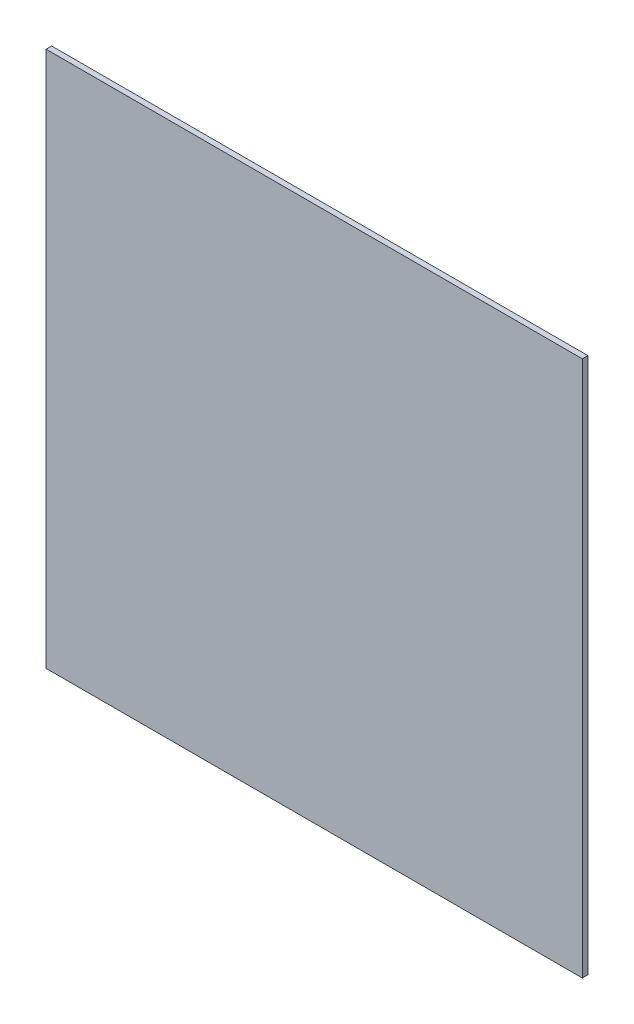
SolidWorks part; units mm, degrees
material "Al homeycomb"
ref_plane "Front Plane" through (0, 0, 0) normal (0, 0, 1) x (1, 0, 0)
ref_plane "Top Plane" through (0, 0, 0) normal (0, 1, 0) x (1, 0, 0)
ref_plane "Right Plane" through (0, 0, 0) normal (1, 0, 0) x (0, 0, -1)
sketch "Sketch1" plane through (0, 0, 0) normal (0, 0, 1) x (1, 0, 0)
  line L1 (-1200, -1200) -> (1200, -1200)
  line L2 (-1200, -1200) -> (-1200, 1200)
  line L3 (-1200, 1200) -> (1200, 1200)
  line L4 (1200, -1200) -> (1200, 1200)
  line L5 (-1200, -1200) -> (1200, 1200) construction
  line L6 (-1200, 1200) -> (1200, -1200) construction
  point P0 (0, 0)
  dimension "D1" = 2400
  dimension "D2" = 2400
extrude "Boss-Extrude1" add sketch "Sketch1" along normal blind 25
